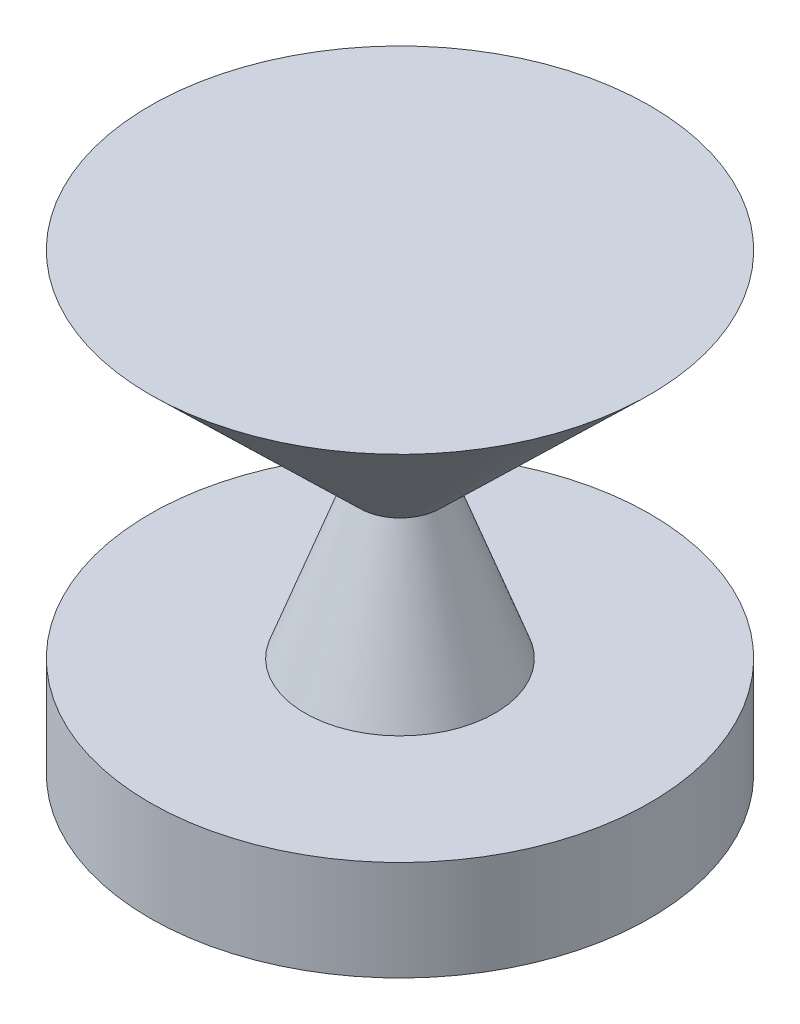
SolidWorks part; units mm, degrees
ref_plane "Front Plane" through (0, 0, 0) normal (0, 0, 1) x (1, 0, 0)
ref_plane "Top Plane" through (0, 0, 0) normal (0, 1, 0) x (1, 0, 0)
ref_plane "Right Plane" through (0, 0, 0) normal (1, 0, 0) x (0, 0, -1)
sketch "Sketch1" plane through (0, 0, 0) normal (0, 0, 1) x (1, 0, 0)
  line L0 (0, 0) -> (0, 6.6192) construction
  line L1 (0, 0) -> (-5, 0)
  line L2 (-5, 0) -> (-5, 2)
  line L3 (-5, 2) -> (-1.9, 2)
  line L4 (-1.9, 2) -> (-0.8081, 5)
  line L6 (0, 5) -> (0, 0)
  line L7 (-0.8081, 5) -> (-5, 9.0669)
  line L8 (-5, 9.0669) -> (0, 9.0669)
  line L9 (0, 9.0669) -> (0, 5)
  point P3 (-1.9, 7.6341)
  point P10 (-1.9, 7.6341)
  point P11 (-5, 9.0669)
  dimension "D1" = 5
  dimension "D2" = 2
  dimension "D3" = 3.1
  dimension "D4" = 110
  dimension "D5" = 3
  dimension "D6" = 5
  dimension "D7" = 4.0669
revolve "Revolve1" add sketch "Sketch1" angle 360 about L0
